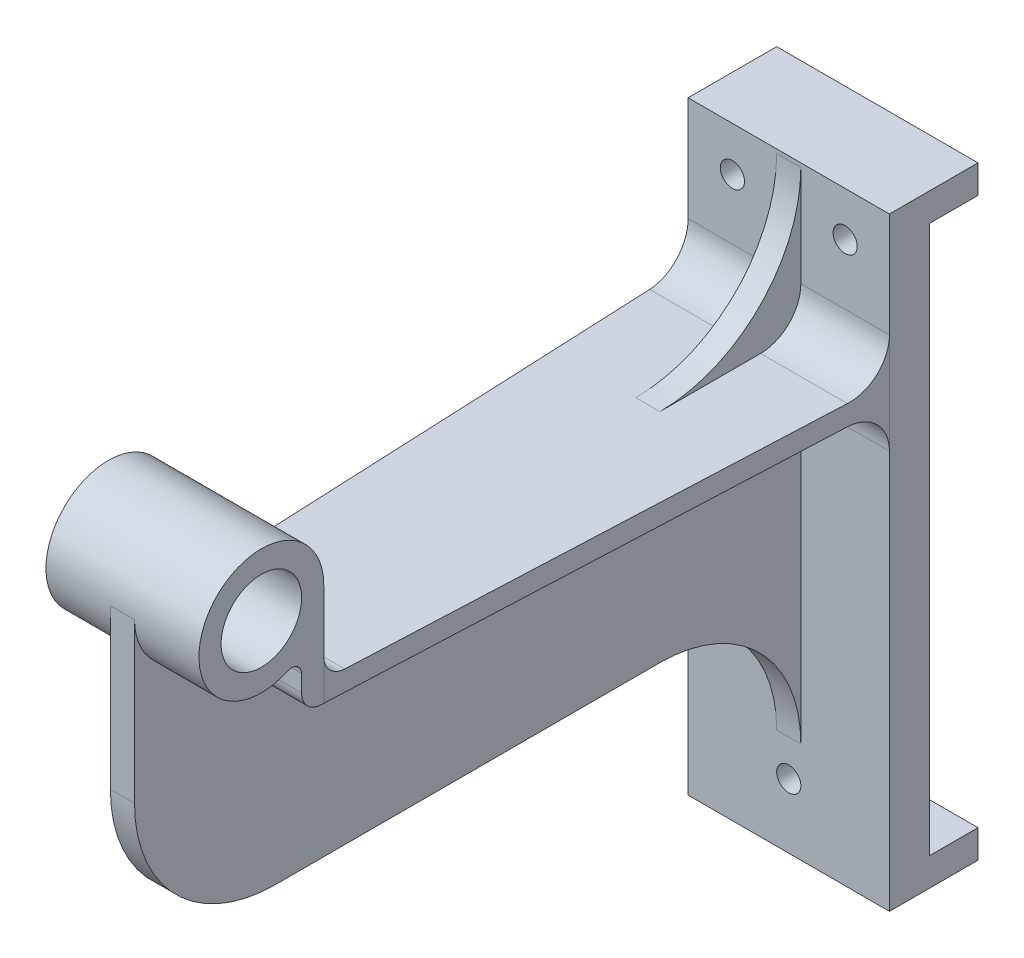
SolidWorks part; units mm, degrees
ref_plane "Front Plane" through (0, 0, 0) normal (0, 0, 1) x (1, 0, 0)
ref_plane "Top Plane" through (0, 0, 0) normal (0, 1, 0) x (1, 0, 0)
ref_plane "Right Plane" through (0, 0, 0) normal (1, 0, 0) x (0, 0, -1)
sketch "Sketch1" plane through (0, 0, 0) normal (1, 0, 0) x (0, 0, -1)
  line L0 (20, -136) -> (44, -136)
  line L1 (44, -136) -> (44, -150)
  line L2 (44, -150) -> (0, -150)
  line L3 (55, 0) -> (-55, 0) construction
  line L4 (44, 150) -> (0, 150)
  line L5 (44, 136) -> (44, 150)
  line L6 (20, 136) -> (44, 136)
  line L7 (0, 150) -> (0, -150)
  line L8 (20, 136) -> (20, -136)
  dimension "D1" = 300
  dimension "D2" = 44
  dimension "D3" = 14
  dimension "D4" = 24
extrude "Boss-Extrude1" add sketch "Sketch1" along normal blind 100
ref_plane "Plane1" through (50, 0, 0) normal (1, 0, 0) x (0, 0, -1)
sketch "Sketch4" plane through (50, 0, 0) normal (1, 0, 0) x (0, 0, -1)
  line L0 (44, 136) -> (44, 150) construction
  line L1 (44, 150) -> (0, 150) construction
  line L2 (-269, 119) -> (-269, 68)
  line L3 (-269, 68) -> (-280, 68)
  line L4 (-280, 68) -> (-280, 95.3146)
  arc A0 (-269, 119) -> (-280, 95.3146) centre (-300, 119) ccw
  circle A1 centre (-300, 119) radius 20
  dimension "D1" = 62
  dimension "D2" = 40
  dimension "D3" = 344
  dimension "D4" = 82
extrude "Boss-Extrude3" add sketch "Sketch4" along normal mid plane 76 separate body
sketch "Sketch7" plane through (0, 68, 0) normal (0, -1, 0) x (1, 0, 0)
  line L0 (88, 280) -> (12, 280) construction
  line L1 (88, 280) -> (12, 280)
  line L2 (12, 280) -> (12, 269)
  line L3 (12, 269) -> (0, 0)
  line L4 (0, 0) -> (0, -5)
  line L5 (0, 0) -> (0, -44) construction
  line L6 (0, -5) -> (100, -5)
  line L7 (100, 0) -> (100, -44) construction
  line L8 (100, -5) -> (100, 0)
  line L9 (100, 0) -> (88, 269)
  line L10 (88, 269) -> (88, 280)
  line L11 (100, 0) -> (0, 0) construction
  dimension "D1" = 5
extrude "Boss-Extrude4" add sketch "Sketch7" against normal blind 10
fillet "Fillet1" radius 10 2 edges at (50, 78, 269) (50, 68, 280)
fillet "Fillet2" radius 5 1 edges at (50, 95.3146, 280)
sketch "Sketch8" plane through (50, 0, 0) normal (1, 0, 0) x (0, 0, -1)
  line L0 (0, 150) -> (0, 78) construction
  line L1 (0, 78) -> (-259, 78) construction
  line L2 (0, 78) -> (-70, 78)
  line L3 (0, 148) -> (0, 78)
  arc A0 (-70, 78) -> (0, 148) centre (-70, 148) ccw
  point P2 (-84.6453, 160.964)
  dimension "D1" = 140
extrude "Boss-Extrude5" add sketch "Sketch8" along normal mid plane 12
fillet "Fillet3" radius 20 3 edges at (50, 68, 0) (22, 78, 0) (78, 78, 0)
sketch "Sketch10" plane through (50, 0, 0) normal (1, 0, 0) x (0, 0, -1)
  line L0 (-331, 119) -> (-331, 40)
  line L1 (-261, -30) -> (-70, -30)
  line L2 (0, 48) -> (0, -150) construction
  line L3 (0, -150) -> (44, -150) construction
  line L4 (-269, 68) -> (-270, 68) construction
  line L5 (-20, 68) -> (-269, 68) construction
  line L6 (-280, 86.2739) -> (-280, 78) construction
  line L7 (0, 48) -> (0, -100)
  line L8 (-269, 68) -> (-270, 68)
  line L9 (-20, 68) -> (-269, 68)
  line L10 (-280, 86.2739) -> (-280, 78)
  arc A0 (-269, 119) -> (-287.0833, 90.8192) centre (-300, 119) ccw construction
  arc A1 (-331, 119) -> (-287.0833, 90.8192) centre (-300, 119) ccw
  arc A2 (-331, 40) -> (-261, -30) centre (-261, 40) ccw
  arc A3 (-70, -30) -> (0, -100) centre (-70, -100) cw
  arc A4 (0, 48) -> (-20, 68) centre (-20, 48) ccw construction
  arc A5 (-280, 78) -> (-270, 68) centre (-270, 78) ccw construction
  arc A6 (-280, 86.2739) -> (-287.0833, 90.8192) centre (-285, 86.2739) ccw construction
  arc A7 (0, 48) -> (-20, 68) centre (-20, 48) ccw
  arc A8 (-280, 78) -> (-270, 68) centre (-270, 78) ccw
  arc A9 (-280, 86.2739) -> (-287.0833, 90.8192) centre (-285, 86.2739) ccw
  point P14 (0, -100)
  dimension "D2" = 70
  dimension "D1" = 120
extrude "Boss-Extrude6" add sketch "Sketch10" along normal mid plane 12
hole_wizard "Hole1" positions "Sketch11" profile "Sketch12" legacy
sketch "Sketch11" plane through (0, 0, 0) normal (0, 0, 1) x (1, 0, 0)
  line L0 (100, -150) -> (0, -150) construction
  line L1 (100, 150) -> (100, 98) construction
  line L2 (88, 150) -> (12, 150) construction
  line L3 (0, 150) -> (0, 98) construction
  line L4 (50, -150) -> (50, -86.3613) construction
  point P0 (50, -118)
  point P2 (22, 128)
  point P4 (78, 128)
  point P21 (0, 0)
  dimension "D1" = 32
  dimension "D2" = 22
  dimension "D3" = 22
  dimension "D4" = 22
  dimension "D5" = 22
sketch "Sketch12" plane through (50, -118, 0) normal (1, 0, 0) x (0, -1, 0)
  line L0 (0, 0) -> (0, 44)
  line L1 (0, 44) -> (6, 44)
  line L2 (6, 44) -> (6, 0)
  line L3 (6, 0) -> (0, 0)
  line L4 (0, 110) -> (0, -10) construction
  dimension "Diameter" = 12
  dimension "Depth" = 44
